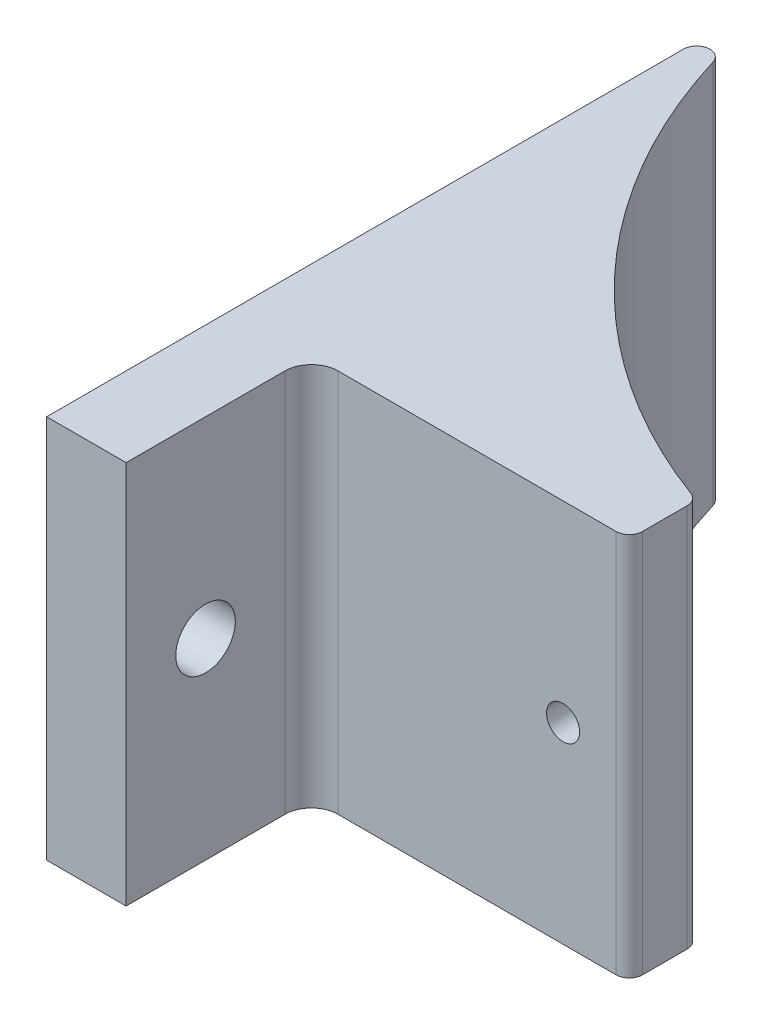
SolidWorks part; units mm, degrees
material "3D printed plastic"
ref_plane "Front Plane" through (0, 0, 0) normal (0, 0, 1) x (1, 0, 0)
ref_plane "Top Plane" through (0, 0, 0) normal (0, 1, 0) x (1, 0, 0)
ref_plane "Right Plane" through (0, 0, 0) normal (1, 0, 0) x (0, 0, -1)
sketch "Sketch1" plane through (0, 0, 0) normal (0, 1, 0) x (1, 0, 0)
  line L0 (-45, -13.4164) -> (-45, -61.5)
  line L1 (-16, -47.5) -> (-37, -47.5)
  line L2 (-39, -49.5) -> (-39, -61.5)
  line L3 (-45, -61.5) -> (-39, -61.5)
  line L4 (-15, -43.1277) -> (-15, -46.5)
  arc A0 (-43.0435, -13.1247) -> (-15.6522, -42.1902) centre (0, 0) ccw
  arc A1 (-15.6522, -42.1902) -> (-15, -43.1277) centre (-16, -43.1277) cw
  arc A2 (-45, -13.4164) -> (-43.0435, -13.1247) centre (-44, -13.4164) cw
  arc A3 (-39, -49.5) -> (-37, -47.5) centre (-37, -49.5) cw
  arc A4 (-15, -46.5) -> (-16, -47.5) centre (-16, -46.5) cw
  point P11 (-45, 0)
  point P14 (-39, -49.5)
  dimension "D1" = 45
  dimension "D5" = 1
  dimension "D6" = 2
  dimension "D2" = 30
  dimension "D3" = 12
  dimension "D4" = 6
  dimension "D7" = 47.5
extrude "Boss-Extrude1" add sketch "Sketch1" along normal mid plane 29
sketch "Sketch2" plane through (-39, 0, 0) normal (1, 0, 0) x (0, 0, -1)
  line L0 (-49.5, 14.5) -> (-49.5, -14.5) construction
  line L1 (-55.5, 0) -> (-61.5, 0) construction
  line L2 (-61.5, 14.5) -> (-61.5, -14.5) construction
  circle A0 centre (-55.5, 0) radius 2.25
  dimension "D1" = 6
  dimension "D2" = 4.5
extrude "Cut-Extrude1" cut sketch "Sketch2" against normal through all
sketch "Sketch3" plane through (0, 0, 47.5) normal (0, 0, 1) x (1, 0, 0)
  line L1 (-20, 0) -> (0, 0) construction
  circle A0 centre (-20, 0) radius 1.25
  dimension "D1" = 20
  dimension "D2" = 2.5
extrude "Cut-Extrude2" cut sketch "Sketch3" against normal through all and the other way through all
